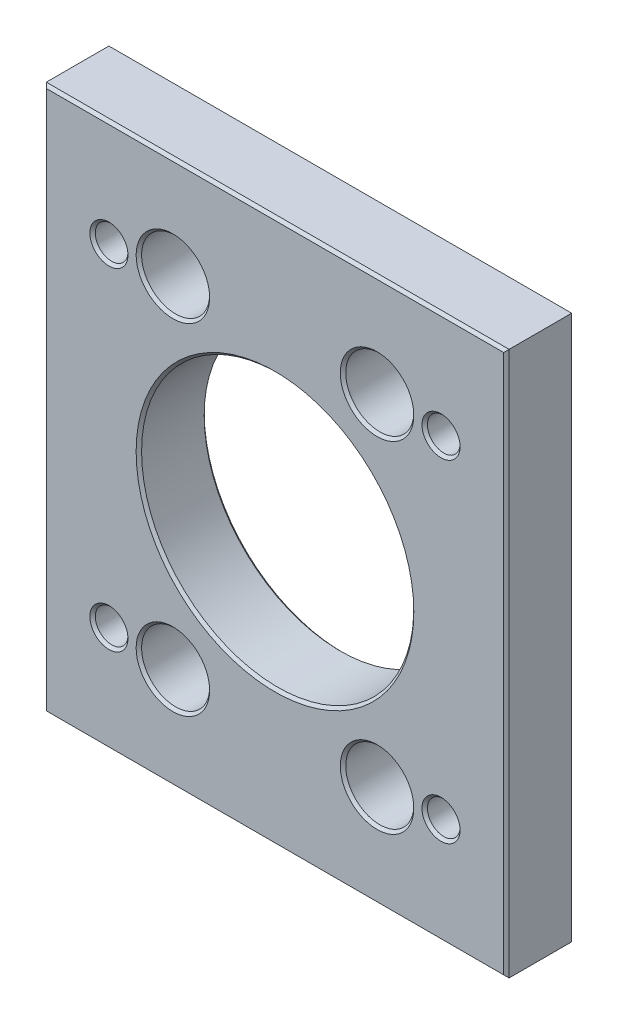
SolidWorks part; units mm, degrees
material "1060 Alloy"
ref_plane "Front Plane" through (0, 0, 0) normal (0, 0, 1) x (1, 0, 0)
ref_plane "Top Plane" through (0, 0, 0) normal (0, 1, 0) x (1, 0, 0)
ref_plane "Right Plane" through (0, 0, 0) normal (1, 0, 0) x (0, 0, -1)
sketch "Sketch1" plane through (0, 0, 0) normal (0, 0, 1) x (1, 0, 0)
  line L0 (-15.494, 15.494) -> (15.494, 15.494) construction
  line L1 (-21.59, -25.4) -> (21.59, -25.4)
  line L2 (-21.59, -25.4) -> (-21.59, 25.4)
  line L3 (-21.59, 25.4) -> (21.59, 25.4)
  line L4 (21.59, -25.4) -> (21.59, 25.4)
  line L5 (-21.59, -25.4) -> (21.59, 25.4) construction
  line L6 (-21.59, 25.4) -> (21.59, -25.4) construction
  line L7 (15.494, 15.494) -> (15.494, -15.494) construction
  line L8 (15.494, -15.494) -> (-15.494, -15.494) construction
  line L9 (-15.494, -15.494) -> (-15.494, 15.494) construction
  line L10 (-15.494, 15.494) -> (15.494, -15.494) construction
  line L11 (15.494, 15.494) -> (-15.494, -15.494) construction
  line L12 (-9.525, 15.875) -> (-9.525, -15.875) construction
  line L13 (-9.525, -15.875) -> (9.525, -15.875) construction
  line L14 (9.525, -15.875) -> (9.525, 15.875) construction
  line L15 (9.525, 15.875) -> (-9.525, 15.875) construction
  line L16 (-9.525, 15.875) -> (9.525, -15.875) construction
  line L17 (9.525, 15.875) -> (-9.525, -15.875) construction
  circle A0 centre (-15.494, 15.494) radius 1.524
  circle A1 centre (-9.525, 15.875) radius 3.175
  circle A2 centre (-15.494, -15.494) radius 1.524
  circle A3 centre (-9.525, -15.875) radius 3.175
  circle A4 centre (9.525, -15.875) radius 3.175
  circle A5 centre (15.494, -15.494) radius 1.524
  circle A6 centre (9.525, 15.875) radius 3.175
  circle A7 centre (15.494, 15.494) radius 1.524
  circle A8 centre (0, 0) radius 12.7
  point P0 (0, 0)
  point P22 (0, 0)
  point P23 (0, 0)
  dimension "D3" = 3.048
  dimension "D6" = 6.35
  dimension "D9" = 25.4
  dimension "D1" = 43.18
  dimension "D2" = 50.8
  dimension "D4" = 30.988
  dimension "D5" = 30.988
  dimension "D7" = 19.05
  dimension "D8" = 31.75
extrude "Boss-Extrude1" add sketch "Sketch1" along normal blind 6.35
chamfer "Chamfer1" distance 0.254 angle 45 26 edges at (17.018, 15.494, 0) (17.018, -15.494, 0) (-6.35, -15.875, 0) (-6.35, 15.875, 0) (0, 25.4, 0) (-21.59, 0, 0) (0, -25.4, 0) (21.59, 0, 0) (-13.97, 15.494, 0) (-13.97, -15.494, 0) (12.7, -15.875, 0) (12.7, 15.875, 0) (17.018, 15.494, 6.35) (12.7, 15.875, 6.35) (17.018, -15.494, 6.35) (12.7, -15.875, 6.35) (-6.35, -15.875, 6.35) (-13.97, -15.494, 6.35) (-6.35, 15.875, 6.35) (-13.97, 15.494, 6.35) (0, -25.4, 6.35) (-21.59, 0, 6.35) (0, 25.4, 6.35) (21.59, 0, 6.35) (12.7, 0, 0) (12.7, 0, 6.35)
